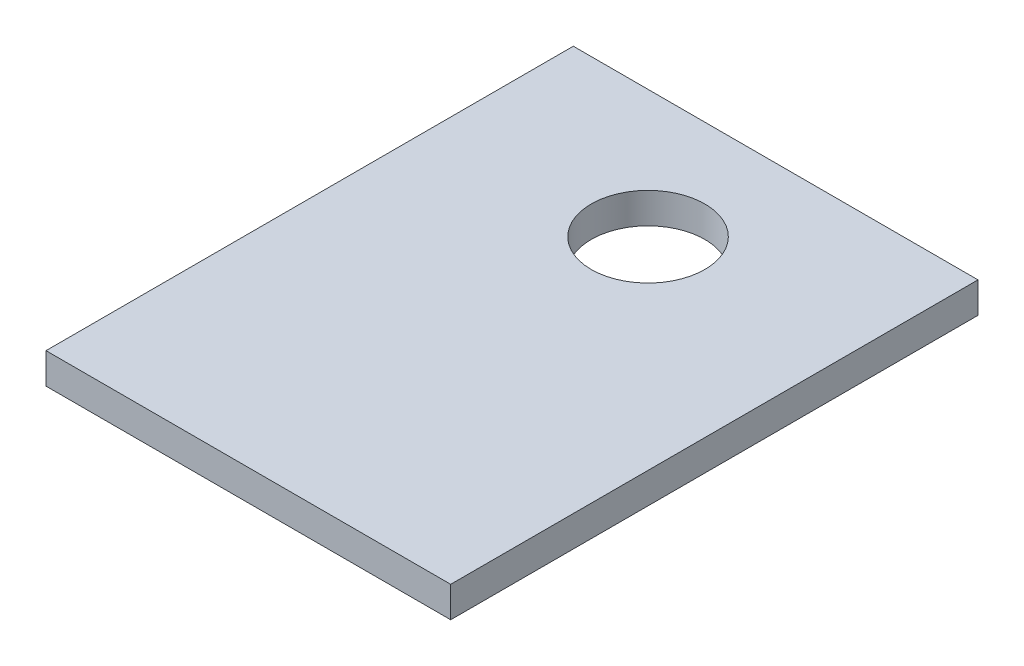
SolidWorks part; units mm, degrees
material "ABS"
ref_plane "Front Plane" through (0, 0, 0) normal (0, 0, 1) x (1, 0, 0)
ref_plane "Top Plane" through (0, 0, 0) normal (0, 1, 0) x (1, 0, 0)
ref_plane "Right Plane" through (0, 0, 0) normal (1, 0, 0) x (0, 0, -1)
sketch "Sketch1" plane through (0, 0, 0) normal (0, 1, 0) x (1, 0, 0)
  line L5 (0, 0) -> (65.8133, 0)
  line L6 (0, 0) -> (0, 85.7542)
  line L7 (0, 85.7542) -> (65.8133, 85.7542)
  line L8 (65.8133, 0) -> (65.8133, 85.7542)
  circle A0 centre (32.9066, 65) radius 9.2364
  point P8 (32.9066, 85.7542)
  dimension "D1" = 65
extrude "Boss-Extrude1" add sketch "Sketch1" along normal blind 5
